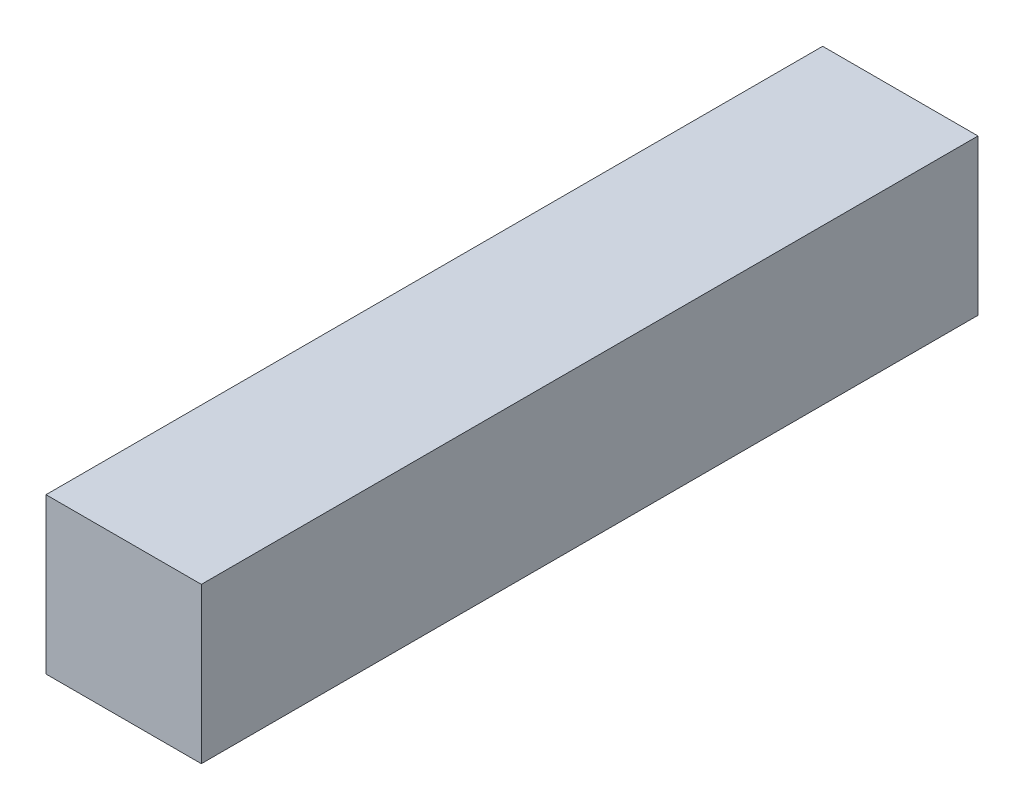
SolidWorks part; units mm, degrees
ref_plane "Front Plane" through (0, 0, 0) normal (0, 0, 1) x (1, 0, 0)
ref_plane "Top Plane" through (0, 0, 0) normal (0, 1, 0) x (1, 0, 0)
ref_plane "Right Plane" through (0, 0, 0) normal (1, 0, 0) x (0, 0, -1)
sketch "Sketch1" plane through (0, 0, 0) normal (0, 0, 1) x (1, 0, 0)
  line L1 (-2.5, -2.5) -> (2.5, -2.5)
  line L2 (-2.5, -2.5) -> (-2.5, 2.5)
  line L3 (-2.5, 2.5) -> (2.5, 2.5)
  line L4 (2.5, -2.5) -> (2.5, 2.5)
  line L5 (-2.5, -2.5) -> (2.5, 2.5) construction
  line L6 (-2.5, 2.5) -> (2.5, -2.5) construction
  point P0 (0, 0)
  dimension "D1" = 5
  dimension "D2" = 5
extrude "Boss-Extrude1" add sketch "Sketch1" along normal blind 25
